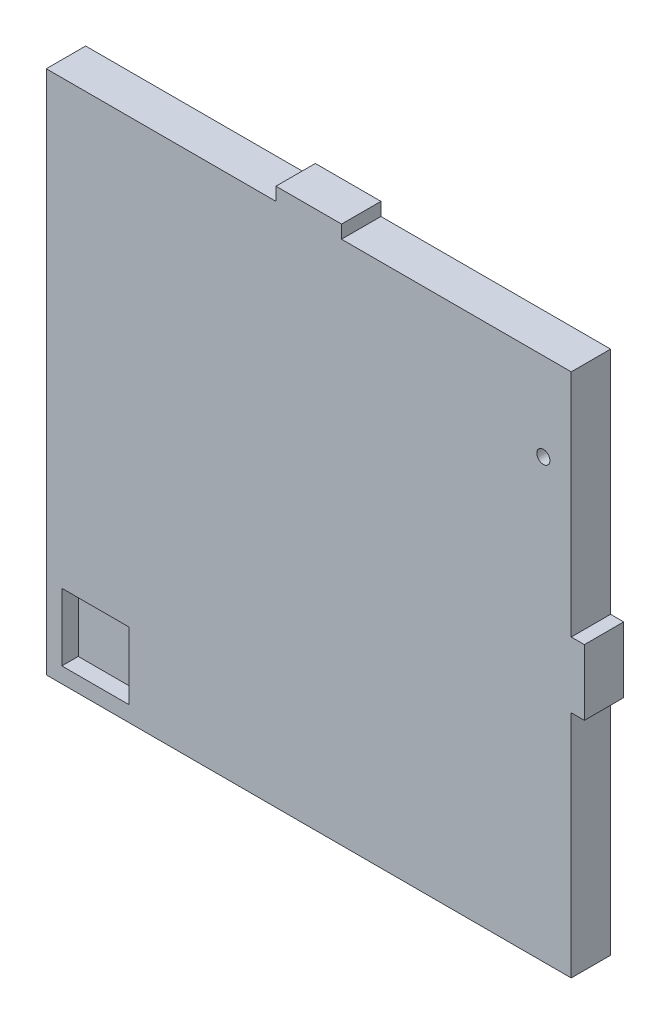
SolidWorks part; units mm, degrees
ref_plane "Front Plane" through (0, 0, 0) normal (0, 0, 1) x (1, 0, 0)
ref_plane "Top Plane" through (0, 0, 0) normal (0, 1, 0) x (1, 0, 0)
ref_plane "Right Plane" through (0, 0, 0) normal (1, 0, 0) x (0, 0, -1)
sketch "Sketch1" plane through (0, 0, 0) normal (0, 0, 1) x (1, 0, 0)
  line L0 (0, 0) -> (69.7, 0)
  line L1 (69.7, 0) -> (90.3, 0)
  line L2 (0, 90.3) -> (0, 69.7)
  line L4 (90.3, 0) -> (160, 0)
  line L5 (160, 0) -> (160, 70)
  line L6 (160, 70) -> (164, 70)
  line L7 (164, 70) -> (164, 90)
  line L8 (164, 90) -> (160, 90)
  line L9 (160, 90) -> (160, 160)
  line L10 (160, 160) -> (90, 160)
  line L11 (90, 160) -> (90, 164)
  line L12 (90, 164) -> (70, 164)
  line L13 (70, 164) -> (70, 160)
  line L14 (70, 160) -> (0, 160)
  line L15 (0, 160) -> (0, 90.3)
  line L19 (0, 69.7) -> (0, 0)
  circle A0 centre (151.5, 133.3) radius 2
  dimension "D1" = 4
extrude "Boss-Extrude1" add sketch "Sketch1" along normal blind 12
sketch "Sketch2" plane through (0, 0, 12) normal (0, 0, 1) x (1, 0, 0)
  line L0 (4.75, 4.75) -> (25.25, 4.75)
  line L1 (25.25, 4.75) -> (25.25, 25.25)
  line L2 (25.25, 25.25) -> (4.75, 25.25)
  line L3 (4.75, 25.25) -> (4.75, 4.75)
extrude "Cut-Extrude1" cut sketch "Sketch2" against normal blind 5
sketch "Sketch4" plane through (0, 0, 0) normal (0, 0, -1) x (-1, 0, 0)
  circle A0 centre (-151.5, 133.3) radius 3.45
  dimension "D1" = 6.9
extrude "Cut-Extrude7" cut sketch "Sketch4" against normal blind 8
